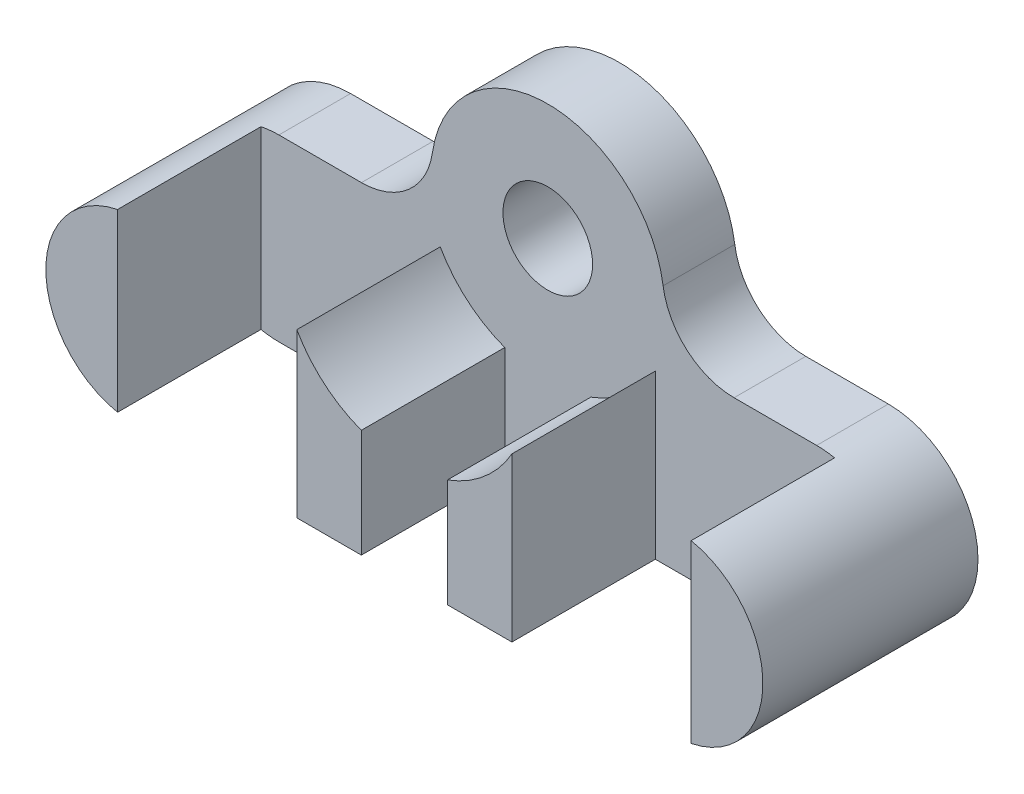
SolidWorks part; units mm, degrees
ref_plane "Front Plane" through (0, 0, 0) normal (0, 0, 1) x (1, 0, 0)
ref_plane "Top Plane" through (0, 0, 0) normal (0, 1, 0) x (1, 0, 0)
ref_plane "Right Plane" through (0, 0, 0) normal (1, 0, 0) x (0, 0, -1)
sketch "Sketch1" plane through (0, 0, 0) normal (0, 0, 1) x (1, 0, 0)
  line L0 (-7.5, -3.75) -> (7.5, -3.75) construction
  line L1 (-7.5, -1.25) -> (-3, -1.25)
  line L2 (-7.5, -6.25) -> (7.5, -6.25)
  line L3 (0, -3.75) -> (0, 0) construction
  line L4 (3, -1.25) -> (7.5, -1.25)
  circle A0 centre (0, 0) radius 1.25
  arc A1 (3, -1.25) -> (-3, -1.25) centre (0, 0) ccw
  arc A2 (-7.5, -1.25) -> (-7.5, -6.25) centre (-7.5, -3.75) ccw
  arc A3 (7.5, -6.25) -> (7.5, -1.25) centre (7.5, -3.75) ccw
  circle A4 centre (0, 0) radius 3.25 construction
  point P7 (0, -3.75)
  dimension "D2" = 2.5
  dimension "D4" = 2.5
  dimension "D3" = 15
  dimension "D1" = 2
extrude "Boss-Extrude1" add sketch "Sketch1" along normal blind 2
sketch "Sketch2" plane through (0, 0, 2) normal (0, 0, 1) x (1, 0, 0)
  line L0 (-3, -1.25) -> (-7.5, -1.25) construction
  line L1 (-3, -1.25) -> (-8, -1.25)
  line L2 (-3, -1.25) -> (-3, -6.25)
  line L3 (-3, -6.25) -> (-8, -6.25)
  line L4 (-8, -1.25) -> (-8, -6.25)
  line L5 (-7.5, -6.25) -> (7.5, -6.25) construction
  line L6 (7.5, -1.25) -> (3, -1.25) construction
  line L7 (3, -1.25) -> (8, -1.25)
  line L8 (3, -1.25) -> (3, -6.25)
  line L9 (3, -6.25) -> (8, -6.25)
  line L10 (8, -1.25) -> (8, -6.25)
  line L11 (-8, -3.75) -> (-10, -3.75) construction
  line L12 (8, -3.75) -> (10, -3.75) construction
  line L16 (-3, -1.25) -> (-7.5, -1.25)
  line L17 (-7.5, -6.25) -> (7.5, -6.25)
  line L18 (7.5, -1.25) -> (3, -1.25)
  line L19 (-3, -1.25) -> (-7.5, -1.25)
  line L20 (-7.5, -6.25) -> (7.5, -6.25)
  line L21 (7.5, -1.25) -> (3, -1.25)
  arc A0 (-7.5, -1.25) -> (-7.5, -6.25) centre (-7.5, -3.75) ccw construction
  arc A1 (7.5, -6.25) -> (7.5, -1.25) centre (7.5, -3.75) ccw construction
  circle A2 centre (0, 0) radius 3.25
  circle A3 centre (0, 0) radius 3.45
  arc A5 (3, -1.25) -> (-3, -1.25) centre (0, 0) ccw
  arc A6 (-7.5, -1.25) -> (-7.5, -6.25) centre (-7.5, -3.75) ccw
  arc A7 (7.5, -6.25) -> (7.5, -1.25) centre (7.5, -3.75) ccw
  arc A8 (3, -1.25) -> (-3, -1.25) centre (0, 0) ccw
  arc A9 (-7.5, -1.25) -> (-7.5, -6.25) centre (-7.5, -3.75) ccw
  arc A10 (7.5, -6.25) -> (7.5, -1.25) centre (7.5, -3.75) ccw
  arc M20 (-7.5, -1.25) -> (-7.5, -6.25) centre (-7.5, -3.75) ccw
  line M21 (-7.5, -6.25) -> (7.5, -6.25)
  arc M22 (7.5, -6.25) -> (7.5, -1.25) centre (7.5, -3.75) ccw
  dimension "D1" = 5
  dimension "D2" = 5
  dimension "D3" = 0
  dimension "D4" = 0.2
extrude "Boss-Extrude2" add sketch "Sketch2" along normal blind 4 contours L4 M20 | A3 L2 L8 M21 | L10 M22
fillet "Fillet1" radius 2 2 edges at (3, -1.25, 1) (-3, -1.25, 1)
sketch "Sketch3" plane through (0, 0, 6) normal (0, 0, 1) x (1, 0, 0)
  line L0 (-3, -6.25) -> (3, -6.25) construction
  line L1 (-1.2, -6.25) -> (1.2, -6.25)
  line L2 (-1.2, -6.25) -> (-1.2, -3.2346)
  line L3 (-1.2, -3.2346) -> (1.2, -3.2346)
  line L4 (1.2, -6.25) -> (1.2, -3.2346)
  line L5 (0, 0) -> (0, -6.25) construction
  arc A0 (-3, -1.7037) -> (3, -1.7037) centre (0, 0) ccw construction
  dimension "D1" = 2.4
extrude "Cut-Extrude1" cut sketch "Sketch3" against normal up to surface (4 mm away) up to face at (1.25, 0, 2)
